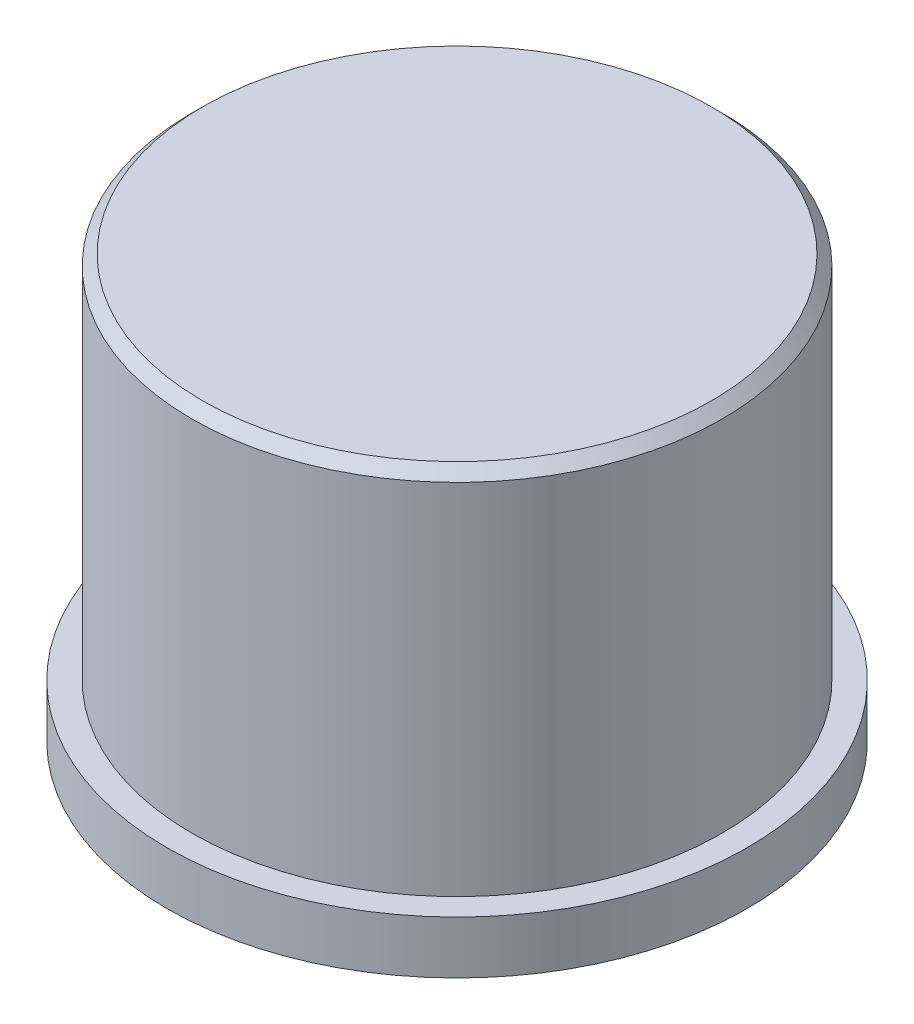
SolidWorks part; units mm, degrees
material "ABS"
ref_plane "Front Plane" through (0, 0, 0) normal (0, 0, 1) x (1, 0, 0)
ref_plane "Top Plane" through (0, 0, 0) normal (0, 1, 0) x (1, 0, 0)
ref_plane "Right Plane" through (0, 0, 0) normal (1, 0, 0) x (0, 0, -1)
sketch "Sketch1" plane through (0, 0, 0) normal (0, 1, 0) x (1, 0, 0)
  circle A0 centre (0, 0) radius 5.5
  dimension "D1" = 11
extrude "Boss-Extrude1" add sketch "Sketch1" along normal blind 1
sketch "Sketch2" plane through (0, 1, 0) normal (0, 1, 0) x (1, 0, 0)
  circle A0 centre (0, 0) radius 5.025
  dimension "D1" = 10.05
extrude "Boss-Extrude2" add sketch "Sketch2" along normal blind 7
sketch "Sketch3" plane through (0, 0, 0) normal (0, -1, 0) x (1, 0, 0)
  line L1 (3.0022, 0) -> (1.5011, 2.6)
  line L2 (1.5011, 2.6) -> (-1.5011, 2.6)
  line L3 (-1.5011, 2.6) -> (-3.0022, 0)
  line L4 (-3.0022, 0) -> (-1.5011, -2.6)
  line L5 (-1.5011, -2.6) -> (1.5011, -2.6)
  line L6 (1.5011, -2.6) -> (3.0022, 0)
  circle A0 centre (0, 0) radius 2.6 construction
  dimension "D1" = 5.2
extrude "Cut-Extrude1" cut sketch "Sketch3" against normal blind 7 contours L1 L2 L3 L4 L5 L6
chamfer "Chamfer1" distance 0.2 angle 45 1 edges at (0, 8, 5.025)
